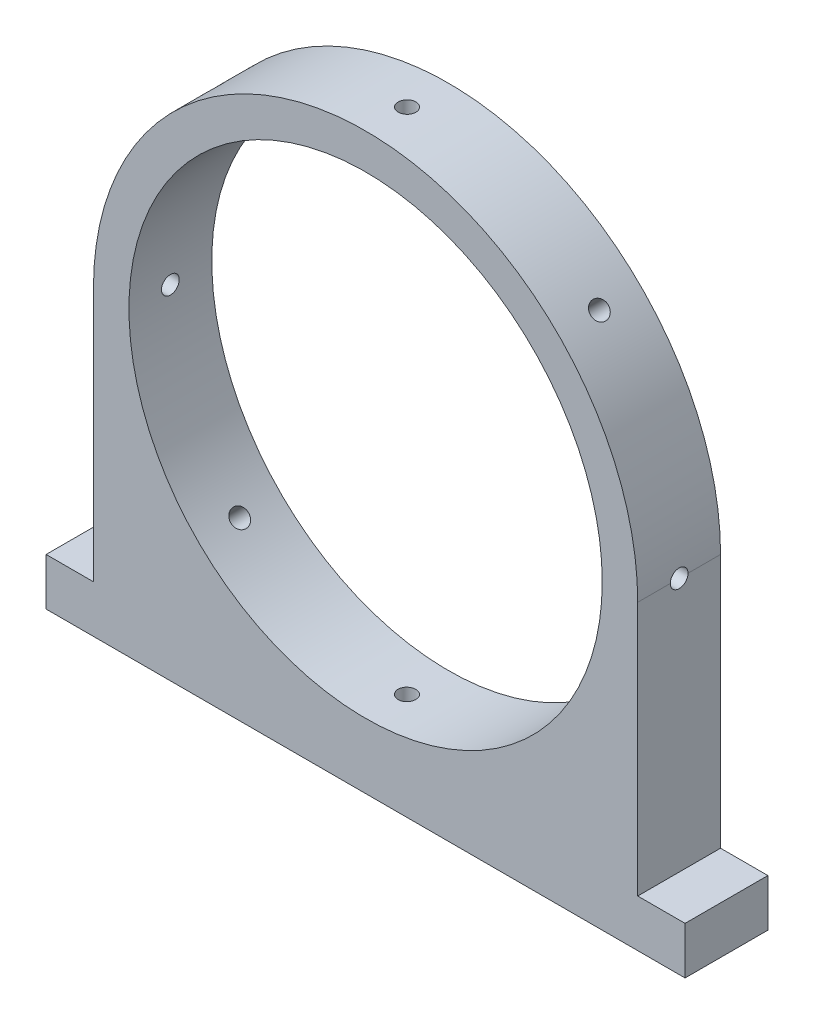
SolidWorks part; units mm, degrees
ref_plane "Front Plane" through (0, 0, 0) normal (0, 0, 1) x (1, 0, 0)
ref_plane "Top Plane" through (0, 0, 0) normal (0, 1, 0) x (1, 0, 0)
ref_plane "Right Plane" through (0, 0, 0) normal (1, 0, 0) x (0, 0, -1)
sketch "Sketch1" plane through (0, 0, 0) normal (0, 0, 1) x (1, 0, 0)
  line L0 (46, -46) -> (54, -46)
  line L1 (-46, 0) -> (-46, -46)
  line L2 (-46, -46) -> (-54, -46)
  line L3 (-54, -46) -> (-54, -51)
  line L4 (0, 47.5825) -> (0, -51) construction
  line L5 (54, -46) -> (54, -51)
  line L6 (46, 0) -> (46, -46)
  line L7 (-54, -51) -> (54, -51)
  circle A0 centre (0, 0) radius 40
  arc A1 (46, 0) -> (-46, 0) centre (0, 0) ccw
  dimension "D1" = 80
  dimension "D2" = 6
  dimension "D3" = 5
  dimension "D4" = 8
extrude "Boss-Extrude1" add sketch "Sketch1" along normal blind 14
sketch "Sketch2" plane through (0, 0, 0) normal (0, 1, 0) x (1, 0, 0)
  line L0 (-54, -7) -> (54, -7) construction
  line L1 (-54, -14) -> (-54, 0) construction
  line L2 (54, -14) -> (54, 0) construction
  circle A0 centre (0, -7) radius 1.5
  dimension "D1" = 3
extrude "Cut-Extrude1" cut sketch "Sketch2" along normal through all
pattern_circular "CirPattern1" count 8 over 360 about axis through (0, 0, 0) along (0, 0, 1) of "Cut-Extrude1"
sketch "Sketch4" plane through (0, -51, 0) normal (0, -1, 0) x (1, 0, 0)
  line L1 (-54, 0) -> (54, 0)
  line L2 (-54, 0) -> (-54, 14)
  line L3 (-54, 14) -> (54, 14)
  line L4 (54, 0) -> (54, 14)
sketch "Sketch5" plane through (0, -51, 0) normal (0, -1, 0) x (1, 0, 0)
  line L1 (-54, 0) -> (54, 0)
  line L2 (-54, 0) -> (-54, 14)
  line L3 (-54, 14) -> (54, 14)
  line L4 (54, 0) -> (54, 14)
extrude "Boss-Extrude2" add sketch "Sketch5" against normal blind 8
